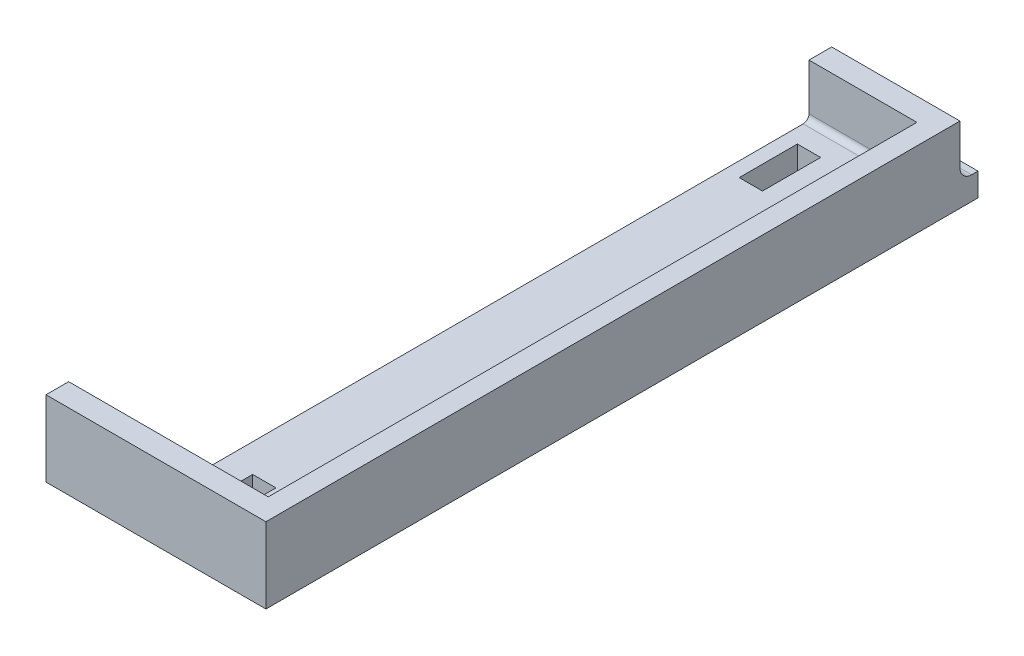
SolidWorks part; units mm, degrees
ref_plane "Front Plane" through (0, 0, 0) normal (0, 0, 1) x (1, 0, 0)
ref_plane "Top Plane" through (0, 0, 0) normal (0, 1, 0) x (1, 0, 0)
ref_plane "Right Plane" through (0, 0, 0) normal (1, 0, 0) x (0, 0, -1)
sketch "Sketch1" plane through (0, 0, 0) normal (0, 1, 0) x (1, 0, 0)
  line L0 (0, 0) -> (0, 3.9)
  line L1 (0, 3.9) -> (20.5, 3.9)
  line L2 (0, 0) -> (37.8, 0)
  line L3 (37.8, 0) -> (37.8, 129.4)
  line L6 (37.8, 129.4) -> (37.8, 132.4)
  line L7 (37.8, 132.4) -> (20.5, 132.4)
  line L9 (20.5, 129.4) -> (37.8, 129.4) construction
  line L11 (15.75, 132.4) -> (15.75, 95.9)
  line L12 (15.75, 95.9) -> (20.5, 95.9)
  line L13 (20.5, 95.9) -> (20.5, 3.9)
  line L14 (20.5, 132.4) -> (15.75, 132.4)
extrude "Boss-Extrude1" add sketch "Sketch1" against normal blind 4
sketch "Sketch2" plane through (0, 0, 0) normal (0, 1, 0) x (1, 0, 0)
  line L0 (0, 3.9) -> (0, 0)
  line L1 (0, 0) -> (37.8, 0)
  line L9 (34.3, 115.4) -> (34.3, 3.9)
  line L10 (34.3, 3.9) -> (0, 3.9)
  line L14 (37.8, 0) -> (37.8, 132.4) construction
  line L15 (37.8, 119.3) -> (37.8, 0)
  line L16 (34.3, 115.4) -> (15.75, 115.4)
  line L17 (15.75, 132.4) -> (15.75, 95.9) construction
  line L18 (15.75, 115.4) -> (15.75, 119.3)
  line L19 (15.75, 119.3) -> (37.8, 119.3)
extrude "Boss-Extrude3" add sketch "Sketch2" along normal blind 9
fillet "Fillet2" radius 2 1 edges at (26.775, 0, -119.3)
sketch "Sketch4" plane through (20.5, 0, 0) normal (-1, 0, 0) x (0, 0, 1)
  line L0 (-95.9, 0) -> (-95.9, -4)
  line L1 (-95.9, -4) -> (-95.9, 0) construction
  line L2 (-95.9, -4) -> (-3.9, -4)
  line L3 (-3.9, -4) -> (-3.9, 0)
  line L4 (-3.9, -4) -> (-3.9, 0) construction
  line L5 (-3.9, 0) -> (-95.9, 0)
extrude "Boss-Extrude4" add sketch "Sketch4" along normal blind 4.75
sketch "Sketch3" plane through (0, 0, 0) normal (0, 1, 0) x (1, 0, 0)
  line L0 (20.62, 9.9209) -> (15.75, 9.9209) construction
  line L4 (18.25, 100.9) -> (18.25, 110.9)
  line L5 (18.25, 110.9) -> (22.25, 110.9)
  line L6 (22.25, 110.9) -> (22.25, 100.9)
  line L8 (26.9895, 0) -> (26.9895, 4.9958) construction
  line L9 (0, 0) -> (37.8, 0) construction
  line L10 (15.75, 115.4) -> (15.75, 3.9) construction
  line L13 (18.25, 100.9) -> (22.25, 100.9)
  line L15 (20.6202, 14.9) -> (24.6202, 14.9)
  line L19 (24.6202, 14.9) -> (24.6198, 4.9419)
  line L20 (24.6198, 4.9419) -> (26.9895, 4.9958) construction
  line L21 (24.6198, 4.9419) -> (20.6198, 4.9419)
  line L22 (20.6198, 4.9419) -> (20.6202, 14.9)
extrude "Cut-Extrude1" cut sketch "Sketch3" against normal blind 10
fillet "Fillet3" radius 1 3 edges at (25.025, 0, -3.9) (25.025, 0, -115.4) (34.3, 0, -59.65)
sketch "Sketch5" plane through (0, 0, -132.4) normal (0, 0, -1) x (-1, 0, 0)
  line L1 (-41.1508, 3.7432) -> (-13.8618, 3.7432)
  line L2 (-41.1508, 3.7432) -> (-41.1508, -8.2963)
  line L3 (-41.1508, -8.2963) -> (-13.8618, -8.2963)
  line L4 (-13.8618, 3.7432) -> (-13.8618, -8.2963)
  line L5 (-41.1508, 3.7432) -> (-13.8618, -8.2963) construction
  line L6 (-41.1508, -8.2963) -> (-13.8618, 3.7432) construction
  point P0 (-27.5063, -2.2765)
extrude "Cut-Extrude2" cut sketch "Sketch5" against normal blind 10
